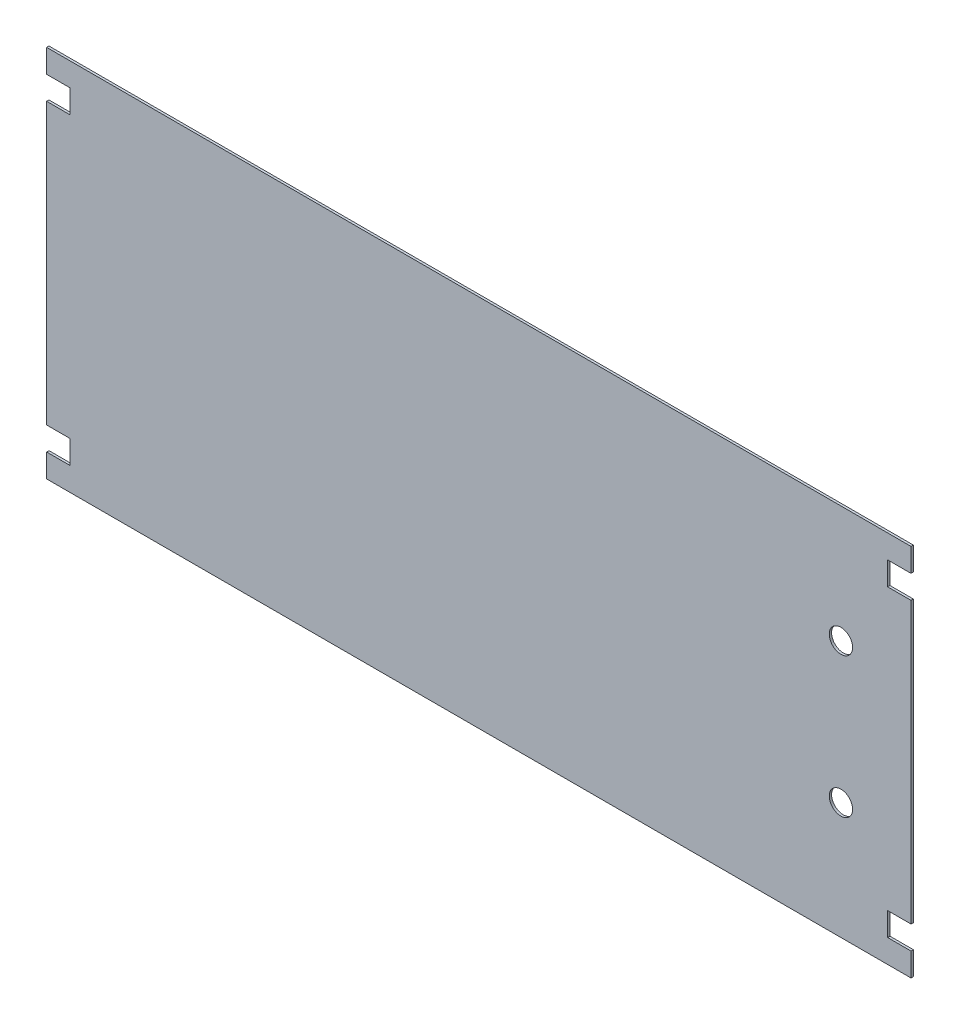
SolidWorks part; units mm, degrees
ref_plane "Front Plane" through (0, 0, 0) normal (0, 0, 1) x (1, 0, 0)
ref_plane "Top Plane" through (0, 0, 0) normal (0, 1, 0) x (1, 0, 0)
ref_plane "Right Plane" through (0, 0, 0) normal (1, 0, 0) x (0, 0, -1)
sketch "Sketch1" plane through (0, 0, 0) normal (0, 0, 1) x (1, 0, 0)
  line L1 (0, 0) -> (370, 0)
  line L2 (0, 0) -> (0, 160)
  line L3 (0, 160) -> (370, 160)
  line L4 (370, 0) -> (370, 160)
  dimension "D1" = 370
  dimension "D2" = 160
extrude "kich_thuoc_tong_quan" add sketch "Sketch1" along normal blind 1
sketch "Sketch2" plane through (0, 0, 1) normal (0, 0, 1) x (1, 0, 0)
  line L0 (0, 160) -> (0, 0) construction
  line L1 (0, 150) -> (10, 150)
  line L2 (0, 150) -> (0, 140)
  line L3 (0, 140) -> (10, 140)
  line L4 (10, 150) -> (10, 140)
  line L5 (370, 160) -> (0, 160) construction
  line L6 (360, 150) -> (360, 140)
  line L7 (360, 150) -> (370, 150)
  line L8 (370, 150) -> (370, 140)
  line L9 (360, 140) -> (370, 140)
  line L10 (360, 20) -> (360, 10)
  line L11 (360, 20) -> (370, 20)
  line L12 (370, 20) -> (370, 10)
  line L13 (360, 10) -> (370, 10)
  line L14 (0, 20) -> (0, 10)
  line L15 (0, 20) -> (10, 20)
  line L16 (10, 20) -> (10, 10)
  line L17 (0, 10) -> (10, 10)
  dimension "D1" = 10
  dimension "D2" = 10
  dimension "D3" = 10
  dimension "D6" = 350
  dimension "D7" = 120
  dimension "D4" = 2
  dimension "D5" = 2
extrude "lo_chot_co_dinh" cut sketch "Sketch2" against normal up to next
sketch "Sketch3" plane through (0, 0, 1) normal (0, 0, 1) x (1, 0, 0)
  line L0 (370, 20) -> (370, 140) construction
  line L5 (370, 160) -> (0, 160) construction
  circle A0 centre (340, 110) radius 5
  circle A1 centre (340, 50) radius 5
  dimension "D1" = 10
  dimension "D4" = 60
  dimension "D2" = 50
  dimension "30" = 30
  dimension "D3" = 2
extrude "lo_thong_khi" cut sketch "Sketch3" against normal up to next
